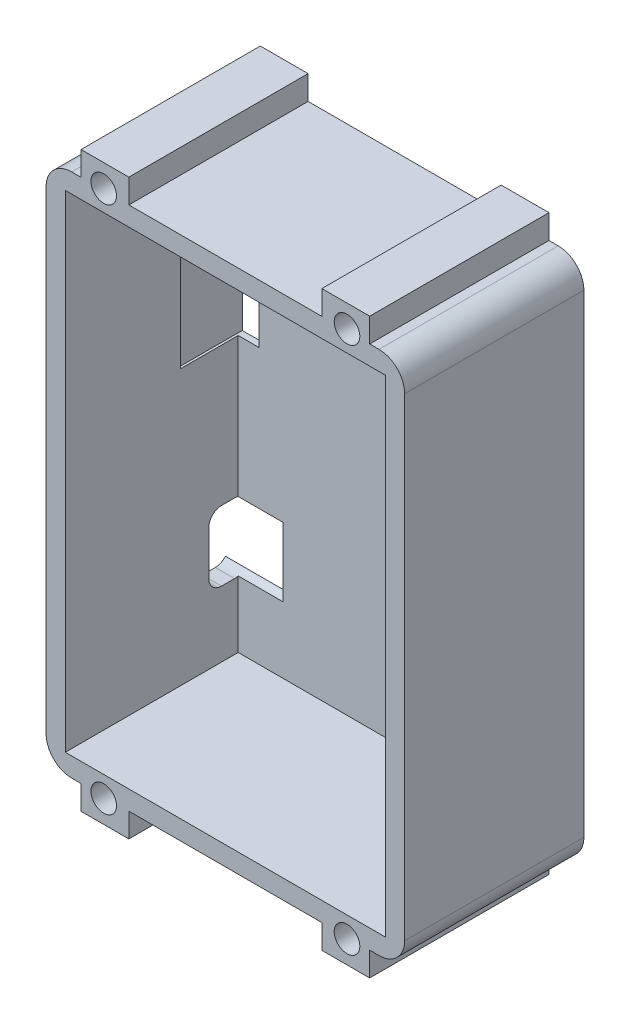
SolidWorks part; units mm, degrees
ref_plane "Alzado" through (0, 0, 0) normal (0, 0, 1) x (1, 0, 0)
ref_plane "Planta" through (0, 0, 0) normal (0, 1, 0) x (1, 0, 0)
ref_plane "Vista lateral" through (0, 0, 0) normal (1, 0, 0) x (0, 0, -1)
sketch "Croquis1" plane through (0, 0, 0) normal (0, 0, 1) x (1, 0, 0)
  line L0 (-24, 41) -> (-22.5441, 41)
  line L1 (-22.5441, 41) -> (-22.5441, 44.7626)
  line L2 (-22.5441, 44.7626) -> (-15.0747, 44.7626)
  line L3 (-15.0747, 44.7626) -> (-15.0747, 41)
  line L4 (-15.0747, 41) -> (15.0747, 41)
  line L5 (15.0747, 41) -> (15.0747, 44.7626)
  line L6 (15.0747, 44.7626) -> (22.5441, 44.7626)
  line L7 (22.5441, 44.7626) -> (22.5441, 41)
  line L8 (22.5441, 41) -> (24, 41)
  line L9 (28, 37) -> (28, -37)
  line L10 (24, -41) -> (22.5441, -41)
  line L11 (22.5441, -41) -> (22.5441, -44.7626)
  line L12 (22.5441, -44.7626) -> (15.0747, -44.7626)
  line L13 (15.0747, -44.7626) -> (15.0747, -41)
  line L14 (15.0747, -41) -> (-15.0747, -41)
  line L15 (-15.0747, -41) -> (-15.0747, -44.7626)
  line L16 (-15.0747, -44.7626) -> (-22.5441, -44.7626)
  line L17 (-22.5441, -44.7626) -> (-22.5441, -41)
  line L18 (-22.5441, -41) -> (-24, -41)
  line L19 (-28, -37) -> (-28, 37)
  line L20 (-25, 38) -> (25, 38)
  line L21 (-25, 38) -> (-25, -38)
  line L22 (-25, -38) -> (25, -38)
  line L23 (25, 38) -> (25, -38)
  line L24 (-25, 38) -> (25, -38) construction
  line L25 (-25, -38) -> (25, 38) construction
  arc A0 (28, 37) -> (24, 41) centre (24, 37) ccw
  arc A1 (24, -41) -> (28, -37) centre (24, -37) ccw
  arc A2 (-28, -37) -> (-24, -41) centre (-24, -37) ccw
  arc A3 (-24, 41) -> (-28, 37) centre (-24, 37) ccw
  point P28 (0, 0)
extrude "Saliente-Extruir1" add sketch "Croquis1" along normal blind 28
sketch "Croquis2" plane through (0, 0, 28) normal (0, 0, 1) x (1, 0, 0)
  line L0 (-19, -41.25) -> (19, -41.25) construction
  line L1 (-19, -41.25) -> (-19, 41.25) construction
  line L2 (-19, 41.25) -> (19, 41.25) construction
  line L3 (19, -41.25) -> (19, 41.25) construction
  line L4 (-19, -41.25) -> (19, 41.25) construction
  line L5 (-19, 41.25) -> (19, -41.25) construction
  circle A0 centre (-19, 41.25) radius 2
  circle A1 centre (19, 41.25) radius 2
  circle A2 centre (-19, -41.25) radius 2
  circle A3 centre (19, -41.25) radius 2
  point P0 (0, 0)
  dimension "D3" = 4
  dimension "D4" = 4
  dimension "D5" = 4
  dimension "D6" = 4
  dimension "D1" = 38
  dimension "D2" = 82.5
extrude "Cortar-Extruir1" cut sketch "Croquis2" against normal blind 28
sketch "Croquis3" plane through (0, 0, 0) normal (0, 0, -1) x (-1, 0, 0)
  line L1 (-25.8976, 38.5566) -> (25.8976, 38.5566)
  line L2 (-25.8976, 38.5566) -> (-25.8976, -38.5566)
  line L3 (-25.8976, -38.5566) -> (25.8976, -38.5566)
  line L4 (25.8976, 38.5566) -> (25.8976, -38.5566)
  line L5 (-25.8976, 38.5566) -> (25.8976, -38.5566) construction
  line L6 (-25.8976, -38.5566) -> (25.8976, 38.5566) construction
  point P0 (0, 0)
extrude "Saliente-Extruir2" add sketch "Croquis3" against normal blind 1
sketch "Croquis4" plane through (0, 0, 0) normal (0, 0, -1) x (-1, 0, 0)
  line L1 (21.7292, 24.1226) -> (25.3601, 24.1226)
  line L2 (21.7292, 24.1226) -> (21.7292, 4.8774)
  line L3 (21.7292, 4.8774) -> (25.3601, 4.8774)
  line L4 (25.3601, 24.1226) -> (25.3601, 4.8774)
  line L5 (21.7292, 24.1226) -> (25.3601, 4.8774) construction
  line L6 (21.7292, 4.8774) -> (25.3601, 24.1226) construction
  point P0 (23.5447, 14.5)
extrude "Cortar-Extruir2" cut sketch "Croquis4" against normal blind 10
sketch "Croquis5" plane through (0, 0, 1) normal (0, 0, 1) x (1, 0, 0)
  line L0 (8.6, -32.2044) -> (8.6, -11.8044)
  line L1 (4.6, -11.8044) -> (4.6, -32.2044)
  line L2 (-25, -38) -> (-25, 4.8774) construction
  arc A0 (4.6, -32.2044) -> (8.6, -32.2044) centre (6.6, -32.2044) ccw
  arc A1 (8.6, -11.8044) -> (4.6, -11.8044) centre (6.6, -11.8044) ccw
  dimension "D1" = 4
  dimension "D2" = 4
  dimension "D3" = 4
  dimension "D4" = 20.4
  dimension "D5" = 29.6
extrude "Saliente-Extruir3" add sketch "Croquis5" along normal blind 3.2
sketch "Croquis6" plane through (0, 0, 4.2) normal (0, 0, 1) x (1, 0, 0)
  circle A0 centre (6.6, -32.2044) radius 0.9
  circle A1 centre (6.6, -11.8044) radius 0.9
  arc A2 (4.6, -32.2044) -> (8.6, -32.2044) centre (6.6, -32.2044) ccw construction
  arc A3 (8.6, -11.8044) -> (4.6, -11.8044) centre (6.6, -11.8044) ccw construction
  dimension "D1" = 1.8
  dimension "D2" = 1.8
  dimension "D3" = 0
  dimension "D4" = 0
extrude "Cortar-Extruir3" cut sketch "Croquis6" against normal blind 10
sketch "Croquis7" plane through (-28, 0, 0) normal (-1, 0, 0) x (0, 0, 1)
  line L1 (3.5898, -27.7241) -> (1.5612, -27.7241)
  line L2 (5.5898, -25.7241) -> (5.5898, -18.8217)
  line L3 (3.5898, -16.8217) -> (1.5612, -16.8217)
  line L4 (-0.4388, -25.7241) -> (-0.4388, -18.8217)
  line L5 (5.5898, -27.7241) -> (-0.4388, -16.8217) construction
  line L6 (5.5898, -16.8217) -> (-0.4388, -27.7241) construction
  arc A0 (3.5898, -27.7241) -> (5.5898, -25.7241) centre (3.5898, -25.7241) ccw
  arc A1 (1.5612, -16.8217) -> (-0.4388, -18.8217) centre (1.5612, -18.8217) ccw
  arc A2 (5.5898, -18.8217) -> (3.5898, -16.8217) centre (3.5898, -18.8217) ccw
  arc A3 (1.5612, -27.7241) -> (-0.4388, -25.7241) centre (1.5612, -25.7241) cw
  point P0 (2.5755, -22.2729)
  dimension "D1" = 2
extrude "Cortar-Extruir4" cut sketch "Croquis7" against normal blind 10
